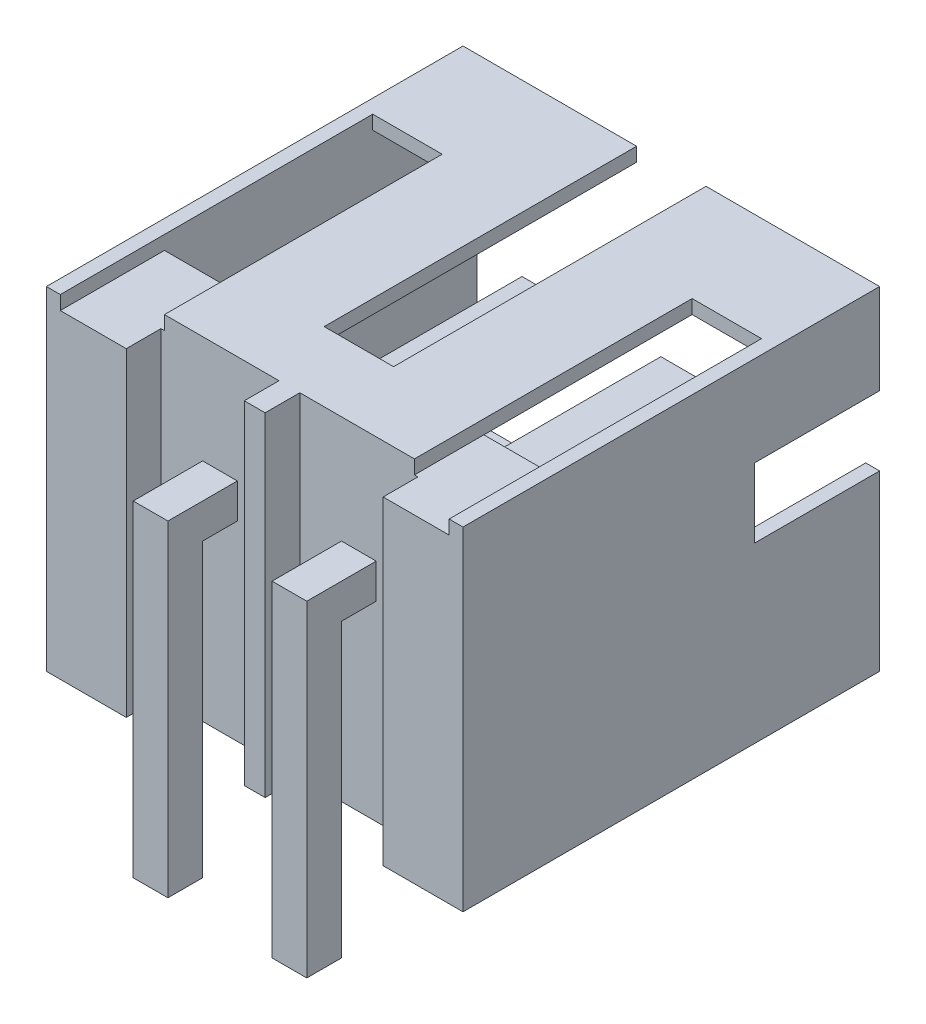
SolidWorks part; units mm, degrees
ref_plane "前视基准面" through (0, 0, 0) normal (0, 0, 1) x (1, 0, 0)
ref_plane "上视基准面" through (0, 0, 0) normal (0, 1, 0) x (1, 0, 0)
ref_plane "右视基准面" through (0, 0, 0) normal (1, 0, 0) x (0, 0, -1)
sketch "草图1" plane through (0, 0, 0) normal (0, 0, 1) x (1, 0, 0)
  line L1 (-3, 2.4) -> (3, 2.4)
  line L2 (-3, 2.4) -> (-3, -2.4)
  line L3 (-3, -2.4) -> (3, -2.4)
  line L4 (3, 2.4) -> (3, -2.4)
  line L5 (-3, 2.4) -> (3, -2.4) construction
  line L6 (-3, -2.4) -> (3, 2.4) construction
  point P0 (0, 0)
extrude "拉伸-薄壁1" add sketch "草图1" along normal blind 6 thin
sketch "草图2" plane through (0, 0, 6) normal (0, 0, 1) x (1, 0, 0)
  line L1 (-2.8, 2.2) -> (2.8, 2.2)
  line L2 (-2.8, 2.2) -> (-2.8, -2.2)
  line L3 (-2.8, -2.2) -> (2.8, -2.2)
  line L4 (2.8, 2.2) -> (2.8, -2.2)
  line L5 (-2.8, 2.2) -> (2.8, -2.2) construction
  line L6 (-2.8, -2.2) -> (2.8, 2.2) construction
  point P0 (0, 0)
extrude "凸台-拉伸1" add sketch "草图2" against normal blind 1.5
sketch "草图3" plane through (0, 2.4, 0) normal (0, 1, 0) x (1, 0, 0)
  line L0 (0, 0) -> (0.5, 0)
  line L1 (3, 0) -> (-3, 0) construction
  line L2 (0.5, 0) -> (0.5, -4.5)
  line L3 (0.5, -4.5) -> (-0.5, -4.5)
  line L4 (-0.5, -4.5) -> (-0.5, 0)
  line L5 (-0.5, 0) -> (0, 0)
  line L6 (-2.8, -6) -> (-2.8, -1.5)
  line L7 (3, -6) -> (-3, -6) construction
  line L8 (-2.8, -1.5) -> (-1.8, -1.5)
  line L9 (-1.8, -1.5) -> (-1.8, -6)
  line L10 (-1.8, -6) -> (-2.8, -6)
  line L11 (0, 0) -> (0, -6) construction
  line L12 (1.8, -6) -> (2.8, -6)
  line L13 (1.8, -1.5) -> (1.8, -6)
  line L14 (2.8, -1.5) -> (1.8, -1.5)
  line L15 (2.8, -6) -> (2.8, -1.5)
extrude "切除-拉伸1" cut sketch "草图3" against normal blind 0.2
sketch "草图4" plane through (-3, 0, 0) normal (-1, 0, 0) x (0, 0, 1)
  line L0 (0, 1.1) -> (2.2426, 1.1) construction
  line L1 (0, 2.4) -> (0, -2.4) construction
  line L2 (6, 2.4) -> (0, 2.4) construction
  line L3 (0, 1.1) -> (1.8, 1.1)
  line L4 (1.8, 1.1) -> (1.8, 0.1)
  line L5 (1.8, 0.1) -> (0, 0.1)
  line L6 (0, 0.1) -> (0, 1.1)
  dimension "D1" = 1.3
extrude "切除-拉伸2" cut sketch "草图4" against normal through all
sketch "草图5" plane through (0, 0, 4.5) normal (0, 0, -1) x (-1, 0, 0)
  line L0 (-3, 0.6) -> (3, 0.6) construction
  line L1 (-3, 0.1) -> (-3, 1.1) construction
  line L2 (3, 0.1) -> (3, 1.1) construction
  line L3 (0, 2.4) -> (0, -2.2) construction
  line L4 (0.5, 2.4) -> (-0.5, 2.4) construction
  line L5 (2.8, -2.2) -> (-2.8, -2.2) construction
  line L6 (1.25, 0.35) -> (0.75, 0.85) construction
  line L7 (-1.25, 0.85) -> (-0.75, 0.85)
  line L8 (-1.25, 0.85) -> (-1.25, 0.35)
  line L9 (-1.25, 0.35) -> (-0.75, 0.35)
  line L10 (-0.75, 0.85) -> (-0.75, 0.35)
  line L11 (-1.25, 0.85) -> (-0.75, 0.35) construction
  line L12 (-1.25, 0.35) -> (-0.75, 0.85) construction
  line L13 (1.25, 0.85) -> (0.75, 0.35) construction
  line L14 (0.75, 0.85) -> (0.75, 0.35)
  line L15 (1.25, 0.35) -> (0.75, 0.35)
  line L16 (1.25, 0.85) -> (1.25, 0.35)
  line L17 (1.25, 0.85) -> (0.75, 0.85)
  point P12 (-1, 0.6)
  point P21 (1, 0.6)
  dimension "D1" = 1
extrude "凸台-拉伸2" add sketch "草图5" along normal blind 3.7
sketch "草图6" plane through (0, 0, 6) normal (0, 0, 1) x (1, 0, 0)
  line L0 (0, 2.4) -> (0, -2.4) construction
  line L1 (1.8, 2.4) -> (-1.8, 2.4) construction
  line L2 (-3, -2.4) -> (3, -2.4) construction
  line L3 (-3, 0.6) -> (3, 0.6) construction
  line L4 (-3, 2.4) -> (-3, -2.4) construction
  line L5 (3, -2.4) -> (3, 2.4) construction
  line L6 (1.25, 0.35) -> (0.75, 0.85) construction
  line L7 (-1.25, 0.85) -> (-0.75, 0.85)
  line L8 (-1.25, 0.85) -> (-1.25, 0.35)
  line L9 (-1.25, 0.35) -> (-0.75, 0.35)
  line L10 (-0.75, 0.85) -> (-0.75, 0.35)
  line L11 (-1.25, 0.85) -> (-0.75, 0.35) construction
  line L12 (-1.25, 0.35) -> (-0.75, 0.85) construction
  line L13 (1.25, 0.85) -> (0.75, 0.35) construction
  line L14 (0.75, 0.85) -> (0.75, 0.35)
  line L15 (1.25, 0.35) -> (0.75, 0.35)
  line L16 (1.25, 0.85) -> (1.25, 0.35)
  line L17 (1.25, 0.85) -> (0.75, 0.85)
  point P12 (-1, 0.6)
  point P21 (1, 0.6)
  dimension "D1" = 1.8
  dimension "D2" = 1
sketch "草图7" plane through (0, 0, 6) normal (0, 0, 1) x (1, 0, 0)
  line L0 (-1.85, 2.4) -> (-1.85, -2.4)
  line L1 (-1.8, 2.4) -> (-2.8, 2.4) construction
  line L2 (-3, -2.4) -> (3, -2.4) construction
  line L3 (-1.85, -2.4) -> (-0.15, -2.4)
  line L4 (-0.15, -2.4) -> (-0.15, 2.4)
  line L5 (1.8, 2.4) -> (-1.8, 2.4) construction
  line L6 (-0.15, 2.4) -> (-1.85, 2.4)
  line L7 (-0.75, 0.85) -> (-0.75, 0.35) construction
  line L8 (-1.25, 0.85) -> (-1.25, 0.35) construction
  line L9 (0, 2.4) -> (0, -2.4) construction
  line L10 (1.85, -2.4) -> (0.15, -2.4)
  line L11 (0.15, -2.4) -> (0.15, 2.4)
  line L12 (0.15, 2.4) -> (1.85, 2.4)
  line L13 (1.85, 2.4) -> (1.85, -2.4)
  dimension "D1" = 0.6
  dimension "D2" = 0.6
extrude "切除-拉伸3" cut sketch "草图7" against normal blind 0.5
extrude "凸台-拉伸3" add sketch "草图6" along normal blind 0.5 and the other way blind 0.5
sketch "草图8" plane through (0, 0.85, 0) normal (0, 1, 0) x (1, 0, 0)
  line L0 (-1.25, -5.5) -> (-1.25, -6.5) construction
  line L1 (-1.25, -6) -> (-0.75, -6)
  line L2 (-1.25, -6) -> (-1.25, -6.5)
  line L3 (-1.25, -6.5) -> (-0.75, -6.5)
  line L4 (-0.75, -6) -> (-0.75, -6.5)
  line L5 (0.75, -5.5) -> (0.75, -6.5) construction
  line L6 (0.75, -6) -> (1.25, -6)
  line L7 (0.75, -6) -> (0.75, -6.5)
  line L8 (0.75, -6.5) -> (1.25, -6.5)
  line L9 (1.25, -6) -> (1.25, -6.5)
  circle A0 centre (-1, -6.25) radius 0.3536 construction
  circle A1 centre (1, -6.25) radius 0.3536 construction
extrude "凸台-拉伸4" add sketch "草图8" against normal blind 4.8
chamfer "倒角1" distance 0.1 angle 45 16 edges at (-1, 0.35, 0.8) (-0.75, 0.6, 0.8) (-1, 0.85, 0.8) (-1.25, 0.6, 0.8) (1, 0.35, 0.8) (1.25, 0.6, 0.8) (1, 0.85, 0.8) (0.75, 0.6, 0.8) (1, -3.95, 6.5) (1.25, -3.95, 6.25) (1, -3.95, 6) (0.75, -3.95, 6.25) (-1, -3.95, 6.5) (-0.75, -3.95, 6.25) (-1, -3.95, 6) (-1.25, -3.95, 6.25)
